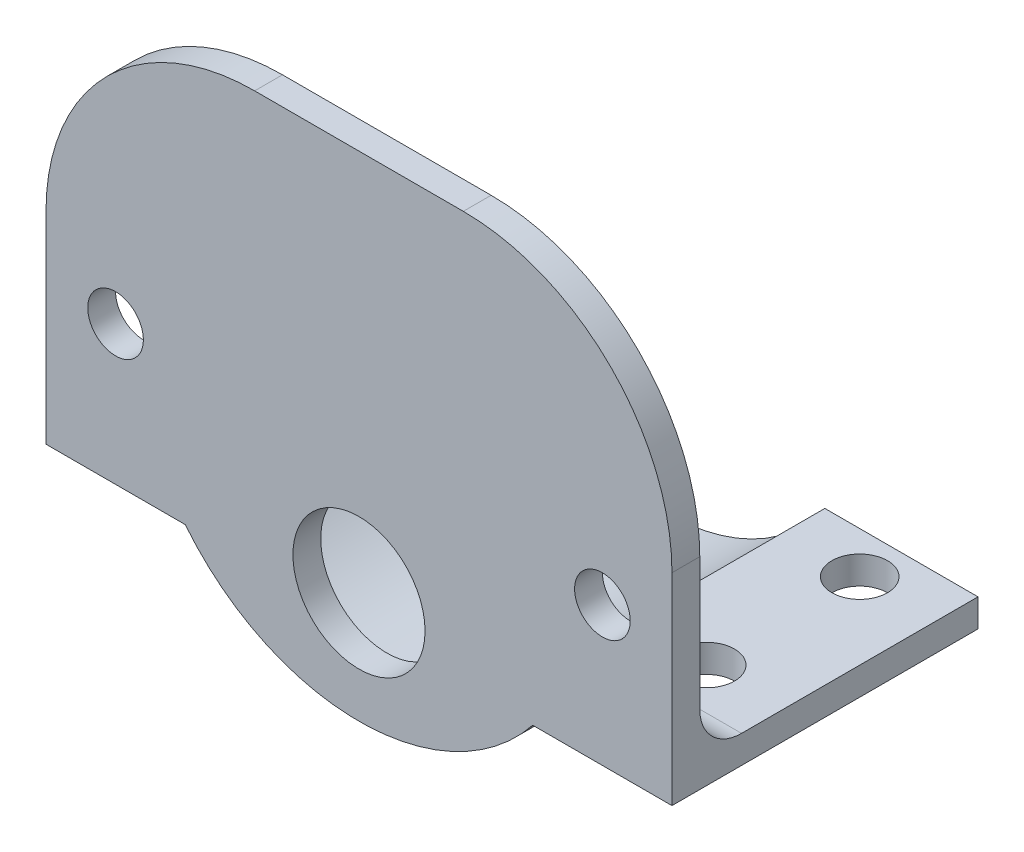
SolidWorks part; units mm, degrees
ref_plane "Front Plane" through (0, 0, 0) normal (0, 0, 1) x (1, 0, 0)
ref_plane "Top Plane" through (0, 0, 0) normal (0, 1, 0) x (1, 0, 0)
ref_plane "Right Plane" through (0, 0, 0) normal (1, 0, 0) x (0, 0, -1)
sketch "Sketch1" plane through (0, 0, 0) normal (0, 0, 1) x (1, 0, 0)
  line L0 (-17.5, 0) -> (17.5, 0) construction
  line L1 (0, 0) -> (0, -8) construction
  line L2 (0, 0) -> (0, 2) construction
  line L3 (-22.5, -8) -> (22.5, -8)
  line L4 (-22.5, 19.5) -> (22.5, 19.5)
  line L5 (-22.5, 19.5) -> (-22.5, -15.5)
  line L6 (-22.5, -15.5) -> (22.5, -15.5)
  line L7 (22.5, 19.5) -> (22.5, -15.5)
  line L8 (-22.5, 19.5) -> (22.5, -15.5) construction
  line L9 (-22.5, -15.5) -> (22.5, 19.5) construction
  circle A0 centre (0, 0) radius 14
  circle A1 centre (17.5, 0) radius 2
  circle A2 centre (-17.5, 0) radius 2
  circle A3 centre (0, -8) radius 4.75
  point P6 (0, 0)
  point P18 (0, -8)
extrude "Boss-Extrude2" add sketch "Sketch1" along normal blind 2 contours A0 L3 L7 L4 L5 A2 A1 | A3 L3 A0 | A3 L3 A0
sketch "Sketch2" plane through (0, 0, 2) normal (0, 0, 1) x (1, 0, 0)
  line L0 (-22.5, -8) -> (-22.5, -10)
  line L1 (22.5, -8) -> (22.5, -10)
  line L7 (12.49, -10) -> (22.5, -10)
  line L8 (-22.5, -10) -> (-12.49, -10)
  line L9 (12.49, -10) -> (22.5, -10)
  line L10 (-22.5, -10) -> (-12.49, -10)
  line L14 (11.4891, -8) -> (22.5, -8)
  line L15 (22.5, -8) -> (22.5, 19.5)
  line L16 (22.5, 19.5) -> (-22.5, 19.5)
  line L17 (-22.5, 19.5) -> (-22.5, -8)
  line L18 (-22.5, -8) -> (-11.4891, -8)
  line L19 (11.4891, -8) -> (22.5, -8)
  line L23 (-22.5, -8) -> (-11.4891, -8)
  arc A4 (-12.49, -10) -> (12.49, -10) centre (0, 0) ccw
  arc A5 (-12.49, -10) -> (12.49, -10) centre (0, 0) ccw
  arc A6 (-11.4891, -8) -> (11.4891, -8) centre (0, 0) ccw
  arc A7 (-11.4891, -8) -> (11.4891, -8) centre (0, 0) ccw
  dimension "D1" = 2
  dimension "D2" = 0
extrude "Boss-Extrude3" add sketch "Sketch2" against normal blind 22
fillet "Fillet1" radius 15 2 edges at (22.5, 19.5, 1) (-22.5, 19.5, 1)
fillet "Fillet2" radius 3 2 edges at (16.9946, -8, 0) (-16.9946, -8, 0)
sketch "Sketch3" plane through (0, -8, 0) normal (0, 1, 0) x (1, 0, 0)
  line L0 (-11.4891, 20) -> (-22.5, 20) construction
  line L1 (22.5, 20) -> (11.4891, 20) construction
  circle A0 centre (-16.9946, 6) radius 2
  circle A1 centre (-16.9946, 17) radius 2
  circle A2 centre (16.9946, 17) radius 2
  circle A3 centre (16.9946, 6) radius 2
  dimension "D1" = 3
  dimension "D3" = 3
  dimension "D2" = 14
  dimension "D4" = 14
extrude "Cut-Extrude1" cut sketch "Sketch3" against normal blind 21
